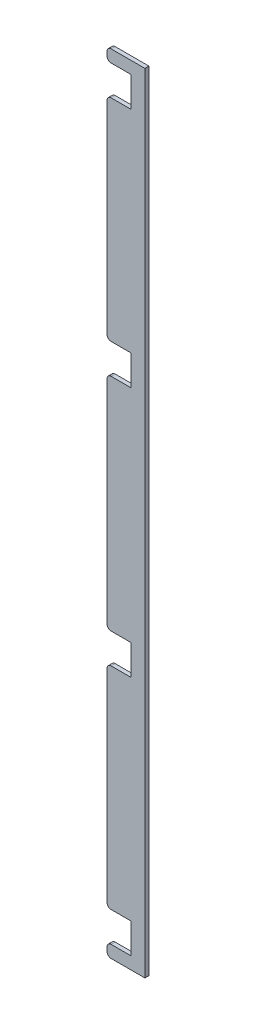
SolidWorks part; units mm, degrees
ref_plane "Front Plane" through (0, 0, 0) normal (0, 0, 1) x (1, 0, 0)
ref_plane "Top Plane" through (0, 0, 0) normal (0, 1, 0) x (1, 0, 0)
ref_plane "Right Plane" through (0, 0, 0) normal (1, 0, 0) x (0, 0, -1)
sketch "Sketch1" plane through (0, 0, 0) normal (0, 0, 1) x (1, 0, 0)
  line L0 (0, -182.5952) -> (-4.5, -182.5952)
  line L2 (0, 13.4048) -> (0, -182.5952)
  line L6 (-4.5, 10.3548) -> (-3.5, 10.3548)
  line L7 (-3.5, 10.3548) -> (-3.5, 2.8548)
  line L9 (-3.5, 2.8548) -> (-4.5, 2.8548)
  line L10 (-4.5, -49.6452) -> (-3.5, -49.6452)
  line L11 (-3.5, -49.6452) -> (-3.5, -57.1452)
  line L12 (-3.5, -57.1452) -> (-4.5, -57.1452)
  line L13 (-4.5, -112.0452) -> (-3.5, -112.0452)
  line L14 (-3.5, -112.0452) -> (-3.5, -119.5452)
  line L15 (-3.5, -119.5452) -> (-4.5, -119.5452)
  line L16 (-4.5, -172.0452) -> (-3.5, -172.0452)
  line L17 (-3.5, -172.0452) -> (-3.5, -179.5452)
  line L18 (-3.5, -179.5452) -> (-4.5, -179.5452)
  line L87 (0, -74.1952) -> (0, -94.9952) construction
  line L100 (-8.4, 10.3548) -> (-4.5, 10.3548)
  line L101 (-4.5, 10.3548) -> (-4.5, 2.8548)
  line L102 (-4.5, 2.8548) -> (-8.4, 2.8548)
  line L103 (-9.4, 1.8548) -> (-9.4, -48.6452)
  line L104 (-8.4, -49.6452) -> (-4.5, -49.6452)
  line L105 (-4.5, -49.6452) -> (-4.5, -57.1452)
  line L106 (-4.5, -57.1452) -> (-8.4, -57.1452)
  line L107 (-9.4, -58.1452) -> (-9.4, -111.0452)
  line L108 (-8.4, -112.0452) -> (-4.5, -112.0452)
  line L109 (-4.5, -112.0452) -> (-4.5, -119.5452)
  line L110 (-4.5, -119.5452) -> (-8.4, -119.5452)
  line L111 (-9.4, -120.5452) -> (-9.4, -171.0452)
  line L112 (-8.4, -172.0452) -> (-4.5, -172.0452)
  line L113 (-4.5, -172.0452) -> (-4.5, -179.5452)
  line L114 (-4.5, -179.5452) -> (-8.4, -179.5452)
  line L115 (-9.4, -180.5452) -> (-9.4, -181.5952)
  line L116 (-8.4, -182.5952) -> (-4.5, -182.5952)
  line L117 (-4.5, -182.5952) -> (-4.5, -191.5952)
  line L118 (-4.5, -191.5952) -> (78.5, -191.5952)
  line L119 (78.5, -191.5952) -> (78.5, -182.5952)
  line L120 (78.5, -182.5952) -> (82.4, -182.5952)
  line L121 (83.4, -181.5952) -> (83.4, -180.5452)
  line L122 (82.4, -179.5452) -> (78.5, -179.5452)
  line L123 (78.5, -179.5452) -> (78.5, -172.0452)
  line L124 (78.5, -172.0452) -> (82.4, -172.0452)
  line L125 (83.4, -171.0452) -> (83.4, -120.5452)
  line L126 (82.4, -119.5452) -> (78.5, -119.5452)
  line L127 (78.5, -119.5452) -> (78.5, -112.0452)
  line L128 (78.5, -112.0452) -> (82.4, -112.0452)
  line L129 (83.4, -111.0452) -> (83.4, -58.1452)
  line L130 (82.4, -57.1452) -> (78.5, -57.1452)
  line L131 (78.5, -57.1452) -> (78.5, -49.6452)
  line L132 (78.5, -49.6452) -> (82.4, -49.6452)
  line L133 (83.4, -48.6452) -> (83.4, 1.8548)
  line L134 (82.4, 2.8548) -> (78.5, 2.8548)
  line L135 (78.5, 2.8548) -> (78.5, 10.3548)
  line L136 (78.5, 10.3548) -> (82.4, 10.3548)
  line L137 (83.4, 11.3548) -> (83.4, 12.4048)
  line L138 (82.4, 13.4048) -> (78.5, 13.4048)
  line L139 (78.5, 13.4048) -> (78.5, 22.4048)
  line L140 (78.5, 22.4048) -> (-4.5, 22.4048)
  line L141 (-4.5, 22.4048) -> (-4.5, 13.4048)
  line L142 (-4.5, 13.4048) -> (-8.4, 13.4048)
  line L143 (-9.4, 12.4048) -> (-9.4, 11.3548)
  line L144 (-8.4, 10.3548) -> (-4.5, 10.3548)
  line L145 (-4.5, 10.3548) -> (-4.5, 2.8548)
  line L146 (-4.5, 2.8548) -> (-8.4, 2.8548)
  line L147 (-9.4, 1.8548) -> (-9.4, -48.6452)
  line L148 (-8.4, -49.6452) -> (-4.5, -49.6452)
  line L149 (-4.5, -49.6452) -> (-4.5, -57.1452)
  line L150 (-4.5, -57.1452) -> (-8.4, -57.1452)
  line L151 (-9.4, -58.1452) -> (-9.4, -111.0452)
  line L152 (-8.4, -112.0452) -> (-4.5, -112.0452)
  line L153 (-4.5, -112.0452) -> (-4.5, -119.5452)
  line L154 (-4.5, -119.5452) -> (-8.4, -119.5452)
  line L155 (-9.4, -120.5452) -> (-9.4, -171.0452)
  line L156 (-8.4, -172.0452) -> (-4.5, -172.0452)
  line L157 (-4.5, -172.0452) -> (-4.5, -179.5452)
  line L158 (-4.5, -179.5452) -> (-8.4, -179.5452)
  line L159 (-9.4, -180.5452) -> (-9.4, -181.5952)
  line L160 (-8.4, -182.5952) -> (-4.5, -182.5952)
  line L186 (0, 13.4048) -> (-8.4, 13.4048)
  line L187 (-9.4, 12.4048) -> (-9.4, 11.3548)
  arc A40 (-8.4, 2.8548) -> (-9.4, 1.8548) centre (-8.4, 1.8548) ccw
  arc A41 (-9.4, -48.6452) -> (-8.4, -49.6452) centre (-8.4, -48.6452) ccw
  arc A42 (-8.4, -57.1452) -> (-9.4, -58.1452) centre (-8.4, -58.1452) ccw
  arc A43 (-9.4, -111.0452) -> (-8.4, -112.0452) centre (-8.4, -111.0452) ccw
  arc A44 (-8.4, -119.5452) -> (-9.4, -120.5452) centre (-8.4, -120.5452) ccw
  arc A45 (-9.4, -171.0452) -> (-8.4, -172.0452) centre (-8.4, -171.0452) ccw
  arc A46 (-8.4, -179.5452) -> (-9.4, -180.5452) centre (-8.4, -180.5452) ccw
  arc A47 (-9.4, -181.5952) -> (-8.4, -182.5952) centre (-8.4, -181.5952) ccw
  arc A48 (82.4, -182.5952) -> (83.4, -181.5952) centre (82.4, -181.5952) ccw
  arc A49 (83.4, -180.5452) -> (82.4, -179.5452) centre (82.4, -180.5452) ccw
  arc A50 (82.4, -172.0452) -> (83.4, -171.0452) centre (82.4, -171.0452) ccw
  arc A51 (83.4, -120.5452) -> (82.4, -119.5452) centre (82.4, -120.5452) ccw
  arc A52 (82.4, -112.0452) -> (83.4, -111.0452) centre (82.4, -111.0452) ccw
  arc A53 (83.4, -58.1452) -> (82.4, -57.1452) centre (82.4, -58.1452) ccw
  arc A54 (82.4, -49.6452) -> (83.4, -48.6452) centre (82.4, -48.6452) ccw
  arc A55 (83.4, 1.8548) -> (82.4, 2.8548) centre (82.4, 1.8548) ccw
  arc A56 (82.4, 10.3548) -> (83.4, 11.3548) centre (82.4, 11.3548) ccw
  arc A57 (83.4, 12.4048) -> (82.4, 13.4048) centre (82.4, 12.4048) ccw
  arc A58 (-8.4, 13.4048) -> (-9.4, 12.4048) centre (-8.4, 12.4048) ccw
  arc A59 (-9.4, 11.3548) -> (-8.4, 10.3548) centre (-8.4, 11.3548) ccw
  arc A60 (-8.4, 2.8548) -> (-9.4, 1.8548) centre (-8.4, 1.8548) ccw
  arc A61 (-9.4, -48.6452) -> (-8.4, -49.6452) centre (-8.4, -48.6452) ccw
  arc A62 (-8.4, -57.1452) -> (-9.4, -58.1452) centre (-8.4, -58.1452) ccw
  arc A63 (-9.4, -111.0452) -> (-8.4, -112.0452) centre (-8.4, -111.0452) ccw
  arc A64 (-8.4, -119.5452) -> (-9.4, -120.5452) centre (-8.4, -120.5452) ccw
  arc A65 (-9.4, -171.0452) -> (-8.4, -172.0452) centre (-8.4, -171.0452) ccw
  arc A66 (-8.4, -179.5452) -> (-9.4, -180.5452) centre (-8.4, -180.5452) ccw
  arc A67 (-9.4, -181.5952) -> (-8.4, -182.5952) centre (-8.4, -181.5952) ccw
  arc A78 (-8.4, 13.4048) -> (-9.4, 12.4048) centre (-8.4, 12.4048) ccw
  arc A79 (-9.4, 11.3548) -> (-8.4, 10.3548) centre (-8.4, 11.3548) ccw
  dimension "D1" = 1
  dimension "D2" = 0
extrude "Boss-Extrude1" add sketch "Sketch1" along normal blind 1
